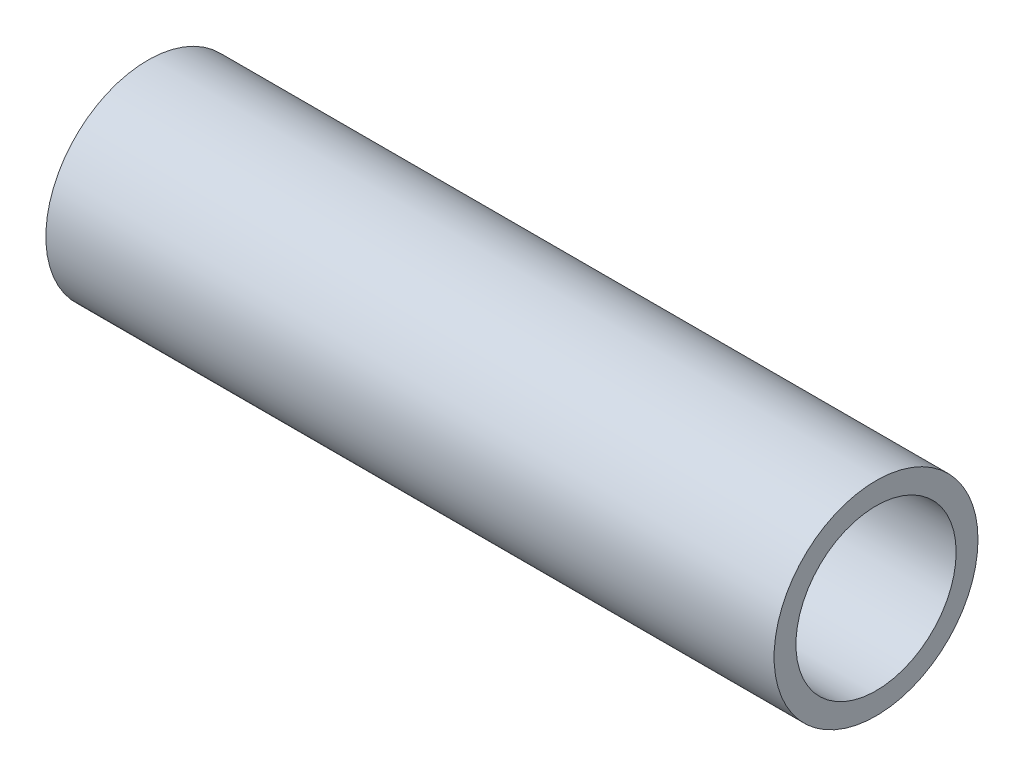
SolidWorks part; units mm, degrees
ref_plane "정면" through (0, 0, 0) normal (0, 0, 1) x (1, 0, 0)
ref_plane "윗면" through (0, 0, 0) normal (0, 1, 0) x (1, 0, 0)
ref_plane "우측면" through (0, 0, 0) normal (1, 0, 0) x (0, 0, -1)
sketch "스케치3" plane through (0, 0, 0) normal (1, 0, 0) x (0, 0, -1)
  circle A0 centre (0, 0) radius 14
  circle A1 centre (0, 0) radius 11
  dimension "D1" = 22
  dimension "D2" = 28
extrude "보스-돌출1" add sketch "스케치3" along normal mid plane 100
